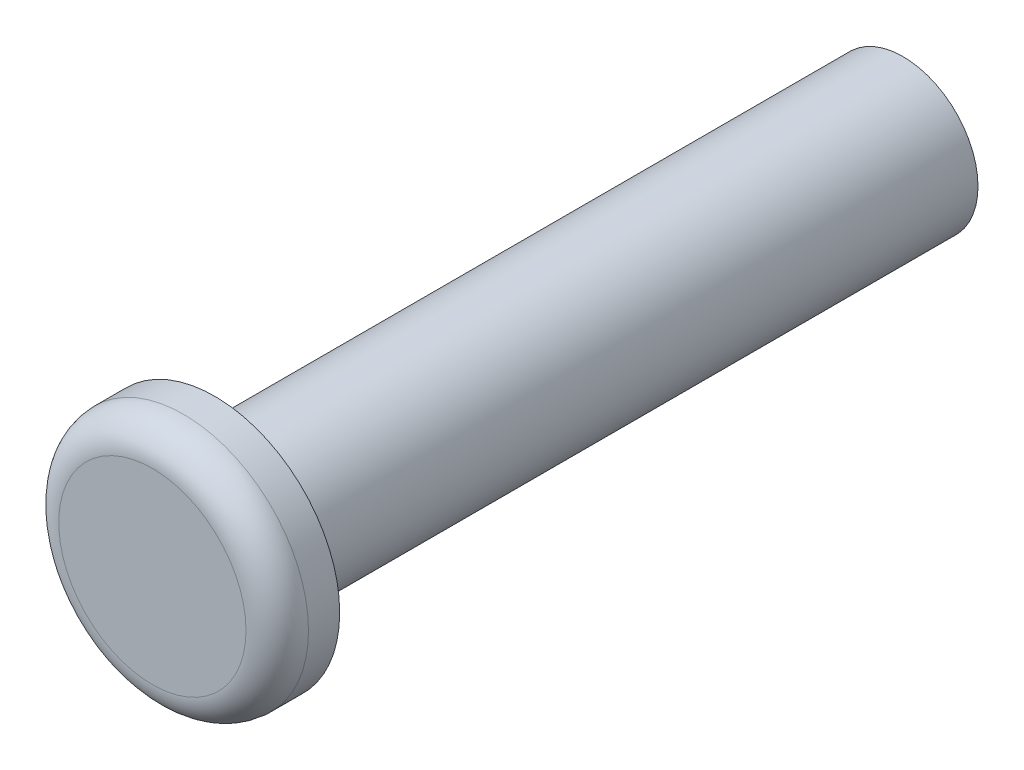
SolidWorks part; units mm, degrees
material "PW20:29:Sc:0:"
ref_plane "Front" through (0, 0, 0) normal (0, 0, 1) x (1, 0, 0)
ref_plane "Top" through (0, 0, 0) normal (0, 1, 0) x (1, 0, 0)
ref_plane "Right" through (0, 0, 0) normal (1, 0, 0) x (0, 0, -1)
sketch "Sketch1" plane through (0, 0, 0) normal (0, 0, 1) x (1, 0, 0)
  circle A0 centre (0, 0) radius 3.81
  dimension "D1" = 7.62
extrude "Base-Extrude" add sketch "Sketch1" against normal blind 35
sketch "Sketch2" plane through (0, 0, 0) normal (0, 0, 1) x (1, 0, 0)
  circle A0 centre (0, 0) radius 6.35
  dimension "D1" = 12.7
extrude "Boss-Extrude1" add sketch "Sketch2" along normal blind 3.175
fillet "Fillet1" radius 1.5875 1 edges at (6.35, 0, 3.175)
